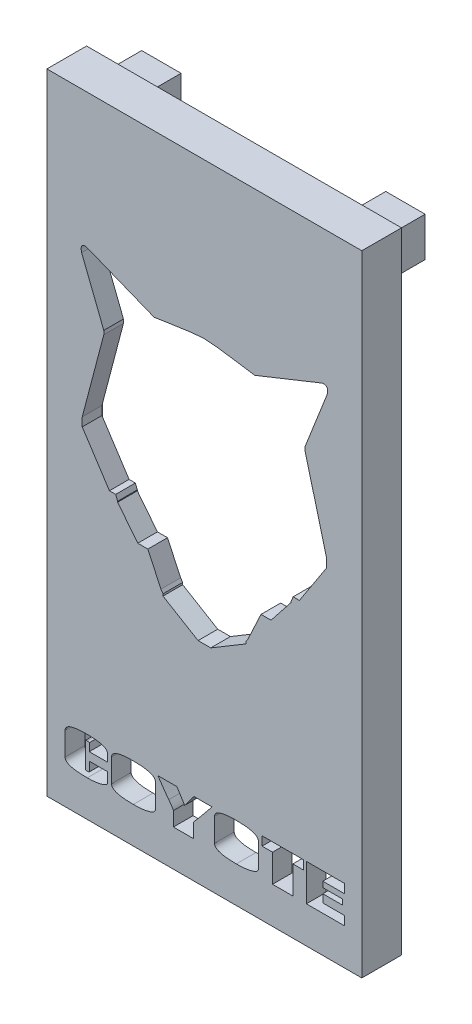
SolidWorks part; units mm, degrees
material "ABS"
ref_plane "Front Plane" through (0, 0, 0) normal (0, 0, 1) x (1, 0, 0)
ref_plane "Top Plane" through (0, 0, 0) normal (0, 1, 0) x (1, 0, 0)
ref_plane "Right Plane" through (0, 0, 0) normal (1, 0, 0) x (0, 0, -1)
sketch "Sketch1" plane through (0, 0, 0) normal (0, 0, 1) x (1, 0, 0)
  line L0 (0, 5.8931) -> (50.8, 5.8931) construction
  line L1 (0, 0) -> (50.8, 0)
  line L2 (0, 0) -> (0, 101.6)
  line L3 (0, 101.6) -> (50.8, 101.6)
  line L4 (50.8, 0) -> (50.8, 101.6)
  line L5 (0, 0) -> (50.8, 0)
  line L6 (0, 0) -> (0, 11.7862)
  line L7 (0, 11.7862) -> (50.8, 11.7862)
  line L8 (50.8, 0) -> (50.8, 11.7862)
  line L9 (25.4, 101.6) -> (25.4, 11.7862) construction
  line L10 (50.8, 50.8) -> (0, 50.8) construction
  dimension "D1" = 101.6
  dimension "D2" = 50.8
extrude "Boss-Extrude1" add sketch "Sketch1" along normal blind 3.175 contours L2 L7 L4 L3 | L6 L0 L8 L7 | L0 L2 L1 L4
ref_plane "Plane5" through (0, 0, 15.24) normal (0, 0, 1) x (1, 0, 0)
sketch "Sketch12"
  line L0 (22.8314, 20.3631) -> (22.8314, 71.1631) construction
  line L1 (35.0907, 71.787) -> (36.1622, 71.3957)
  line L2 (33.5332, 75.5576) -> (44.3723, 79.8969)
  line L3 (41.7167, 69.8549) -> (45.2181, 78.731)
  line L4 (28.6745, 41.3499) -> (25.4088, 42.599)
  line L5 (33.9281, 72.466) -> (39.1813, 74.3847)
  line L6 (39.5352, 74.2729) -> (36.8527, 67.0451)
  line L7 (36.8527, 67.0451) -> (36.5457, 66.2177)
  line L8 (37.2075, 65.2615) -> (38.6023, 66.4344)
  line L9 (38.9404, 66.4344) -> (42.0359, 55.4912)
  line L10 (41.1071, 52.8722) -> (42.0384, 54.7917)
  line L11 (42.0384, 54.7917) -> (42.1172, 54.9541)
  line L12 (42.1172, 54.9541) -> (42.1172, 55.3078)
  line L13 (42.1172, 55.3078) -> (42.0359, 55.4912)
  line L14 (41.7167, 69.8549) -> (41.6413, 69.6639)
  line L15 (41.6413, 69.6639) -> (41.6413, 69.0507)
  line L16 (41.6413, 69.0507) -> (45.1152, 55.8421)
  line L17 (45.1152, 55.8421) -> (45.1152, 54.4389)
  line L18 (45.1152, 54.4389) -> (40.7297, 47.7131)
  line L19 (40.7297, 47.7131) -> (39.7199, 47.7131)
  line L20 (39.7199, 47.7131) -> (39.405, 46.9151)
  line L21 (39.405, 46.9151) -> (39.405, 46.7751)
  line L22 (39.405, 46.7751) -> (36.1622, 42.6658)
  line L23 (36.1622, 42.6658) -> (34.5362, 42.6658)
  line L24 (24.3848, 33.9327) -> (26.4328, 33.9327)
  line L25 (28.6745, 41.3499) -> (28.9066, 41.0664)
  line L26 (28.9066, 41.0664) -> (28.9066, 40.3961)
  line L27 (28.9066, 40.3961) -> (28.3043, 39.5149)
  line L28 (28.3043, 39.5149) -> (28.3043, 39.0684)
  line L29 (28.3043, 39.0684) -> (28.6988, 39.0684)
  line L30 (28.6988, 39.0684) -> (28.9066, 39.2383)
  line L31 (28.9066, 39.2383) -> (29.2159, 39.2383)
  line L32 (29.2159, 39.2383) -> (35.4194, 52.7526)
  line L33 (36.227, 52.7043) -> (36.335, 51.439)
  line L34 (28.1765, 56.1677) -> (30.1632, 57.0025)
  line L35 (30.1632, 57.0025) -> (32.6842, 57.8206)
  line L36 (32.6842, 57.8206) -> (36.1622, 59.6237)
  line L37 (36.9916, 58.672) -> (36.9916, 59.6237)
  line L38 (36.9916, 59.6237) -> (36.8527, 59.7625)
  line L39 (36.8527, 59.7625) -> (36.1622, 59.7625)
  line L40 (36.1622, 59.7625) -> (36.1622, 59.6237)
  line L41 (36.9916, 58.672) -> (34.5362, 55.3078)
  line L42 (34.5362, 55.3078) -> (34.3908, 55.1624)
  line L43 (34.3908, 55.1624) -> (34.3908, 54.9541)
  line L44 (34.3908, 54.9541) -> (34.2296, 54.7929)
  line L45 (34.2296, 54.7929) -> (34.1105, 54.6297)
  line L46 (28.1765, 56.1677) -> (28.1765, 47.7131)
  line L48 (30.1632, 54.6297) -> (34.1105, 54.6297)
  line L50 (30.1632, 54.6297) -> (29.8989, 54.6297)
  line L51 (29.8989, 54.6297) -> (29.8673, 54.4389)
  line L54 (41.1071, 52.8722) -> (40.7297, 53.9768)
  line L55 (39.32, 52.4934) -> (39.6948, 53.5671)
  line L56 (36.7832, 48.8283) -> (36.7832, 47.7131)
  line L57 (36.9916, 47.6502) -> (37.6167, 48.5076)
  line L58 (37.6167, 48.5076) -> (37.6507, 48.605)
  line L59 (37.6507, 48.605) -> (37.7179, 48.7974)
  line L62 (28.8193, 47.8149) -> (28.9066, 48.4626)
  line L63 (28.9066, 48.4626) -> (29.0982, 49.3532)
  line L64 (29.0982, 49.3532) -> (29.2159, 50.3877)
  line L65 (29.2159, 50.3877) -> (29.4417, 51.3784)
  line L66 (29.4417, 51.3784) -> (29.603, 52.432)
  line L67 (29.603, 52.432) -> (29.7662, 53.4698)
  line L68 (29.7662, 53.4698) -> (29.8673, 54.4389)
  line L69 (37.7179, 48.7974) -> (39.32, 52.4934)
  line L70 (39.6948, 53.5671) -> (39.8547, 53.9839)
  line L71 (26.4328, 33.9327) -> (32.0886, 37.317)
  line L72 (0, 101.6) -> (0, 80.01)
  line L73 (32.0886, 37.317) -> (32.0886, 37.6376)
  line L74 (32.0886, 37.6376) -> (32.4184, 38.123)
  line L75 (32.4184, 38.123) -> (34.5362, 42.6658)
  line L76 (36.1622, 71.3957) -> (36.1622, 68.3487)
  line L77 (36.1622, 68.3487) -> (38.3458, 73.1939)
  line L78 (38.3458, 73.1939) -> (35.0907, 71.787)
  line L79 (36.335, 51.439) -> (36.7832, 48.8283)
  line L80 (14.6555, 42.6658) -> (16.2815, 42.6658)
  line L81 (18.3993, 38.123) -> (16.2815, 42.6658)
  line L82 (18.729, 37.6376) -> (18.3993, 38.123)
  line L83 (18.729, 37.317) -> (18.729, 37.6376)
  line L84 (24.3848, 33.9327) -> (18.729, 37.317)
  line L85 (22.1431, 41.3499) -> (25.4088, 42.599)
  line L86 (22.1431, 41.3499) -> (21.9111, 41.0664)
  line L87 (21.9111, 41.0664) -> (21.9111, 40.3961)
  line L88 (21.9111, 40.3961) -> (22.5133, 39.5149)
  line L89 (22.5133, 39.5149) -> (22.5133, 39.0684)
  line L90 (22.5133, 39.0684) -> (22.1188, 39.0684)
  line L91 (22.1188, 39.0684) -> (21.9111, 39.2383)
  line L92 (21.9111, 39.2383) -> (21.6017, 39.2383)
  line L93 (21.6017, 39.2383) -> (15.3982, 52.7526)
  line L94 (14.5906, 52.7043) -> (14.4826, 51.439)
  line L95 (14.4826, 51.439) -> (14.0345, 48.8283)
  line L96 (14.0345, 48.8283) -> (14.0345, 47.7131)
  line L97 (13.2009, 48.5076) -> (13.1669, 48.605)
  line L98 (13.1669, 48.605) -> (13.0998, 48.7974)
  line L99 (13.826, 47.6502) -> (13.2009, 48.5076)
  line L100 (13.0998, 48.7974) -> (11.4977, 52.4934)
  line L101 (11.4977, 52.4934) -> (11.1228, 53.5671)
  line L102 (11.1228, 53.5671) -> (10.9629, 53.9839)
  line L103 (11.4126, 46.7751) -> (14.6555, 42.6658)
  line L104 (11.4126, 46.9151) -> (11.4126, 46.7751)
  line L105 (11.0978, 47.7131) -> (11.4126, 46.9151)
  line L106 (10.0879, 47.7131) -> (11.0978, 47.7131)
  line L107 (5.7024, 54.4389) -> (10.0879, 47.7131)
  line L108 (8.7792, 54.7917) -> (8.7004, 54.9541)
  line L109 (9.7106, 52.8722) -> (8.7792, 54.7917)
  line L110 (8.7004, 55.3078) -> (8.7817, 55.4912)
  line L111 (8.7004, 54.9541) -> (8.7004, 55.3078)
  line L112 (5.7024, 55.8421) -> (5.7024, 54.4389)
  line L113 (9.1763, 69.0507) -> (5.7024, 55.8421)
  line L114 (9.1763, 69.6639) -> (9.1763, 69.0507)
  line L115 (9.101, 69.8549) -> (9.1763, 69.6639)
  line L116 (11.8772, 66.4344) -> (8.7817, 55.4912)
  line L117 (13.6101, 65.2615) -> (12.2153, 66.4344)
  line L118 (13.9649, 67.0451) -> (14.272, 66.2177)
  line L119 (9.101, 69.8549) -> (5.5996, 78.731)
  line L120 (11.2824, 74.2729) -> (13.9649, 67.0451)
  line L121 (17.2845, 75.5576) -> (6.4454, 79.8969)
  line L122 (16.8895, 72.466) -> (11.6364, 74.3847)
  line L123 (22.6411, 56.1677) -> (22.6411, 47.7131)
  line L124 (22.6411, 56.1677) -> (20.6544, 57.0025)
  line L125 (20.6544, 57.0025) -> (18.1334, 57.8206)
  line L126 (18.1334, 57.8206) -> (14.6555, 59.6237)
  line L127 (14.6555, 59.7625) -> (14.6555, 59.6237)
  line L128 (13.9649, 59.7625) -> (14.6555, 59.7625)
  line L129 (13.826, 59.6237) -> (13.9649, 59.7625)
  line L130 (13.826, 58.672) -> (13.826, 59.6237)
  line L131 (13.826, 58.672) -> (16.2815, 55.3078)
  line L132 (16.2815, 55.3078) -> (16.4269, 55.1624)
  line L133 (16.4269, 55.1624) -> (16.4269, 54.9541)
  line L134 (16.4269, 54.9541) -> (16.5881, 54.7929)
  line L135 (16.5881, 54.7929) -> (16.7072, 54.6297)
  line L136 (20.6544, 54.6297) -> (16.7072, 54.6297)
  line L137 (20.6544, 54.6297) -> (20.9187, 54.6297)
  line L138 (20.9187, 54.6297) -> (20.9503, 54.4389)
  line L139 (21.0515, 53.4698) -> (20.9503, 54.4389)
  line L140 (21.2147, 52.432) -> (21.0515, 53.4698)
  line L141 (21.376, 51.3784) -> (21.2147, 52.432)
  line L142 (21.6017, 50.3877) -> (21.376, 51.3784)
  line L143 (21.7195, 49.3532) -> (21.6017, 50.3877)
  line L144 (21.9111, 48.4626) -> (21.7195, 49.3532)
  line L145 (21.9983, 47.8149) -> (21.9111, 48.4626)
  line L146 (14.6555, 68.3487) -> (12.4718, 73.1939)
  line L147 (14.6555, 71.3957) -> (14.6555, 68.3487)
  line L148 (15.7269, 71.787) -> (14.6555, 71.3957)
  line L149 (12.4718, 73.1939) -> (15.7269, 71.787)
  line L150 (0, 0) -> (0, 101.6) construction
  line L151 (50.8, 101.6) -> (45.085, 101.6) construction
  line L152 (0, 101.6) -> (50.8, 101.6) construction
  line L153 (9.7106, 52.8722) -> (10.0879, 53.9768)
  line L155 (0, 101.6) -> (5.715, 101.6) construction
  spline S0 degree 3 poles (28.1765, 47.7131) (28.169, 47.3191) (28.6754, 47.0849) (28.8193, 47.8149) knots 0 0 0 0 1 1 1 1
  spline S1 degree 3 poles (25.4088, 76.6052) (28.138, 76.518) (30.9026, 75.8803) (33.5332, 75.5576) knots 0 0 0 0 1 1 1 1
  spline S2 degree 2 poles (44.3723, 79.8969) (45.5475, 80.1048) (45.2181, 78.731) knots 0 0 0 1 1 1
  spline S3 degree 2 poles (36.7832, 47.7131) (36.771, 47.4639) (36.9916, 47.6502) knots 0 0 0 1 1 1
  spline S4 degree 3 poles (39.1813, 74.3847) (39.8745, 74.7776) (39.8579, 74.7006) (39.5352, 74.2729) knots 0 0 0 0 1 1 1 1
  spline S5 degree 2 poles (32.829, 72.2983) (33.4271, 72.2485) (33.9281, 72.466) knots 0 0 0 1 1 1
  spline S6 degree 2 poles (35.4194, 52.7526) (36.0188, 53.5604) (36.227, 52.7043) knots 0 0 0 1 1 1
  spline S7 degree 3 poles (39.8547, 53.9839) (40.0834, 54.5291) (40.5506, 54.5572) (40.7297, 53.9768) knots 0 0 0 0 1 1 1 1
  spline S8 degree 3 poles (25.4088, 73.4797) (28.138, 73.3925) (30.1985, 72.621) (32.829, 72.2983) knots 0 0 0 0 1 1 1 1
  spline S9 degree 3 poles (38.6023, 66.4344) (38.7999, 66.6114) (38.8666, 66.6853) (38.9404, 66.4344) knots 0 0 0 0 1 1 1 1
  spline S10 degree 3 poles (36.5457, 66.2177) (36.2965, 65.4513) (36.6564, 65.0702) (37.2075, 65.2615) knots 0 0 0 0 1 1 1 1
  spline S11 degree 2 poles (15.3982, 52.7526) (14.7988, 53.5604) (14.5906, 52.7043) knots 0 0 0 1 1 1
  spline S12 degree 2 poles (14.0345, 47.7131) (14.0466, 47.4639) (13.826, 47.6502) knots 0 0 0 1 1 1
  spline S13 degree 3 poles (10.9629, 53.9839) (10.7343, 54.5291) (10.267, 54.5572) (10.0879, 53.9768) knots 0 0 0 0 1 1 1 1
  spline S14 degree 3 poles (12.2153, 66.4344) (12.0177, 66.6114) (11.9511, 66.6853) (11.8772, 66.4344) knots 0 0 0 0 1 1 1 1
  spline S15 degree 3 poles (14.272, 66.2177) (14.5211, 65.4513) (14.1612, 65.0702) (13.6101, 65.2615) knots 0 0 0 0 1 1 1 1
  spline S16 degree 2 poles (6.4454, 79.8969) (5.2701, 80.1048) (5.5996, 78.731) knots 0 0 0 1 1 1
  spline S17 degree 3 poles (11.6364, 74.3847) (10.9431, 74.7776) (10.9598, 74.7006) (11.2824, 74.2729) knots 0 0 0 0 1 1 1 1
  spline S18 degree 2 poles (17.9886, 72.2983) (17.3905, 72.2485) (16.8895, 72.466) knots 0 0 0 1 1 1
  spline S19 degree 3 poles (25.4088, 73.4797) (22.6797, 73.3925) (20.6192, 72.621) (17.9886, 72.2983) knots 0 0 0 0 1 1 1 1
  spline S20 degree 3 poles (25.4088, 76.6052) (22.6797, 76.518) (19.915, 75.8803) (17.2845, 75.5576) knots 0 0 0 0 1 1 1 1
  spline S21 degree 3 poles (22.6411, 47.7131) (22.6486, 47.3191) (22.1422, 47.0849) (21.9983, 47.8149) knots 0 0 0 0 1 1 1 1
  point P42 (22.2043, 56.1677)
  point P83 (25.4088, 76.6052)
  point P97 (25.4088, 33.9327)
other "Pen Sketch1" parameters "D1"=314.7606, "D2"=5.715
other "Pen Sketch2"
extrude "Cut-Extrude3" cut sketch "Sketch12" against normal through all and the other way through all
sketch "Sketch14" plane through (0, 0, 0) normal (0, 0, -1) x (-1, 0, 0)
  line L0 (-50.8, 101.6) -> (-48.26, 101.6)
  line L1 (0, 101.6) -> (-50.8, 101.6) construction
  line L2 (-48.26, 101.6) -> (-48.26, 99.06)
  line L3 (0, 101.6) -> (-2.54, 101.6) construction
  line L4 (-2.54, 101.6) -> (-2.54, 99.06) construction
  line L6 (-48.26, 99.06) -> (-41.91, 99.06)
  line L7 (-48.26, 99.06) -> (-48.26, 92.71)
  line L8 (-48.26, 92.71) -> (-41.91, 92.71)
  line L9 (-41.91, 99.06) -> (-41.91, 92.71)
  line L10 (-2.54, 99.06) -> (-8.89, 99.06)
  line L11 (-2.54, 99.06) -> (-2.54, 92.71)
  line L12 (-2.54, 92.71) -> (-8.89, 92.71)
  line L13 (-8.89, 99.06) -> (-8.89, 92.71)
extrude "Boss-Extrude2" add sketch "Sketch14" along normal blind 9.5758 contours L9 L6 L7 L8 | L10 L13 L12 L11
sketch "Sketch15" plane through (0, 0, 3.175) normal (0, 0, 1) x (1, 0, 0)
  text T0 "COYOTE" font "Haettenschweiler" height in points 24
extrude "Cut-Extrude4" cut sketch "Sketch15" against normal through all
sketch "Sketch16" plane through (0, 0, 3.175) normal (0, 0, 1) x (1, 0, 0)
  line L1 (12.4454, 11.4511) -> (15.1606, 11.4511)
  line L2 (12.4454, 11.4511) -> (12.4454, 6.436)
  line L3 (12.4454, 6.436) -> (15.1606, 6.436)
  line L4 (15.1606, 11.4511) -> (15.1606, 6.436)
  line L5 (29.4712, 11.4511) -> (31.835, 11.4511)
  line L6 (29.4712, 11.4511) -> (29.4712, 6.436)
  line L7 (29.4712, 6.436) -> (31.835, 6.436)
  line L8 (31.835, 11.4511) -> (31.835, 6.436)
extrude "Cut-Extrude5" cut sketch "Sketch16" against normal through all
sketch "Sketch17" plane through (0, 0, 3.175) normal (0, 0, 1) x (1, 0, 0)
  line L0 (36.3986, 5.8931) -> (36.3986, 10.8853) construction
  line L1 (34.7093, 10.8853) -> (36.3986, 10.8853)
  line L2 (34.7093, 10.8853) -> (34.7093, 10.3773)
  line L3 (34.7093, 10.3773) -> (36.3986, 10.3773)
  line L4 (36.3986, 10.8853) -> (36.3986, 10.3773)
  line L6 (39.6748, 10.8853) -> (41.3641, 10.8853)
  line L7 (39.6748, 10.8853) -> (39.6748, 10.3773)
  line L8 (39.6748, 10.3773) -> (41.3641, 10.3773)
  line L9 (41.3641, 10.8853) -> (41.3641, 10.3773)
extrude "Cut-Extrude6" cut sketch "Sketch17" against normal through all
sketch "Sketch18" plane through (0, 0, 3.175) normal (0, 0, 1) x (1, 0, 0)
  line L0 (41.3641, 10.3773) -> (52.3276, 10.3773) construction
  line L1 (47.9822, 10.8853) -> (47.9822, 10.3773)
  line L2 (47.9822, 10.3773) -> (45.1351, 10.3773)
  line L3 (45.1351, 10.3773) -> (45.1351, 10.8853)
  line L4 (45.1351, 10.8853) -> (47.9822, 10.8853)
  line L5 (48.0212, 6.8291) -> (48.0212, 7.3371)
  line L6 (48.0212, 7.3371) -> (45.1351, 7.3371)
  line L7 (45.1351, 8.6232) -> (45.1351, 6.8291) construction
  line L8 (45.1351, 7.3371) -> (45.1351, 6.8291)
  line L9 (45.1351, 6.8291) -> (48.0212, 6.8291)
  line L10 (45.1351, 10.8853) -> (44.6271, 10.8853)
  line L11 (44.6271, 10.8853) -> (44.6271, 9.4797)
  line L12 (44.6271, 9.4797) -> (45.1351, 9.4813)
  line L13 (45.1351, 8.6232) -> (44.6271, 8.6232)
  line L14 (44.6271, 8.6232) -> (44.6271, 6.8291)
  line L15 (44.6271, 6.8291) -> (45.1351, 6.8291)
extrude "Cut-Extrude10" cut sketch "Sketch18" against normal through all contours L4 L3 L2 L1 | L8 L9 L5 L6
sketch "Sketch20" plane through (0, 0, 3.175) normal (0, 0, 1) x (1, 0, 0)
  line L0 (45.1351, 10.3773) -> (44.5001, 10.3773)
  line L1 (45.1351, 10.3773) -> (45.1351, 9.4813)
  line L2 (45.1351, 9.4813) -> (44.5001, 9.4813)
  line L3 (44.5001, 9.4813) -> (44.5001, 10.3773)
  line L4 (45.1351, 8.6232) -> (45.1351, 7.3371)
  line L5 (45.1351, 7.3371) -> (44.5001, 7.3371)
  line L6 (44.5001, 7.3371) -> (44.5001, 8.6232)
  line L7 (44.5001, 8.6232) -> (45.1351, 8.6232)
extrude "Boss-Extrude3" add sketch "Sketch20" against normal blind 3.175
sketch "Sketch22" plane through (0, 0, 0) normal (0, 0, -1) x (-1, 0, 0)
  line L0 (-48.26, 99.06) -> (-2.54, 99.06)
  line L2 (-48.26, 99.06) -> (-48.26, 2.54)
  line L3 (-50.8, 101.6) -> (-50.8, 0)
  line L4 (-50.8, 0) -> (0, 0)
  line L5 (0, 0) -> (0, 101.6)
  line L6 (0, 101.6) -> (-50.8, 101.6)
  line L8 (-2.54, 99.06) -> (-2.54, 2.54)
  line L9 (-2.54, 2.54) -> (-48.26, 2.54)
extrude "Boss-Extrude4" add sketch "Sketch22" along normal blind 3.2258
